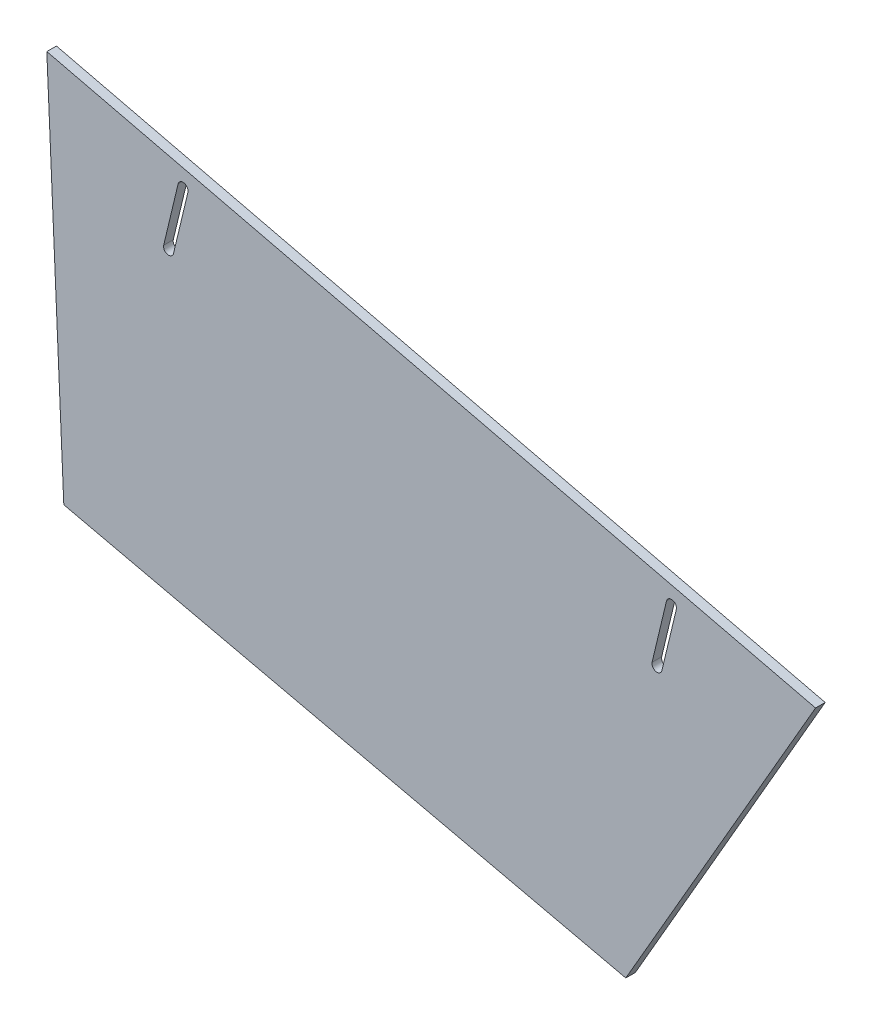
SolidWorks part; units mm, degrees
ref_plane "Front Plane" through (0, 0, 0) normal (1, 0, 0) x (0, 1, 0)
ref_plane "Top Plane" through (0, 0, 0) normal (0, 0, 1) x (0, 1, 0)
ref_plane "Right Plane" through (0, 0, 0) normal (0, 1, 0) x (-1, 0, 0)
sketch "Sketch1" plane through (0, 0, 0) normal (0, 0, 1) x (0, 1, 0)
  line L0 (0, 0) -> (136.832, -79)
  line L1 (136.832, -79) -> (213.48, 241)
  line L2 (213.48, 241) -> (53.6363, 233.9298)
  line L3 (53.6363, 233.9298) -> (0, 0)
  line L4 (167.5089, 190.3141) -> (192.5992, 184.3043) construction
  line L5 (167.998, 192.3563) -> (193.0883, 186.3466)
  line L6 (167.0197, 188.2718) -> (192.11, 182.2621)
  line L7 (0, 0) -> (37.405, 0) construction
  line L8 (175.156, 81) -> (123.8104, 93.2986) construction
  line L9 (118.8132, -12.9869) -> (143.9035, -18.9966) construction
  line L10 (118.324, -15.0291) -> (143.4143, -21.0389)
  line L11 (119.3024, -10.9446) -> (144.3927, -16.9544)
  arc A0 (167.998, 192.3563) -> (167.0197, 188.2718) centre (167.5089, 190.3141) ccw
  arc A1 (192.11, 182.2621) -> (193.0883, 186.3466) centre (192.5992, 184.3043) ccw
  arc A2 (118.324, -15.0291) -> (119.3024, -10.9446) centre (118.8132, -12.9869) cw
  arc A3 (144.3927, -16.9544) -> (143.4143, -21.0389) centre (143.9035, -18.9966) cw
  point P3 (180.054, 187.3092)
  point P17 (131.3583, -15.9918)
  dimension "D9" = 30
  dimension "D1" = 158
  dimension "D2" = 320
  dimension "D3" = 240
  dimension "D4" = 73.47
  dimension "D5" = 160
  dimension "D6" = 30
  dimension "D7" = 60
  dimension "D8" = 4.2
  dimension "D10" = 5
extrude "Boss-Extrude1" add sketch "Sketch1" along normal blind 4
